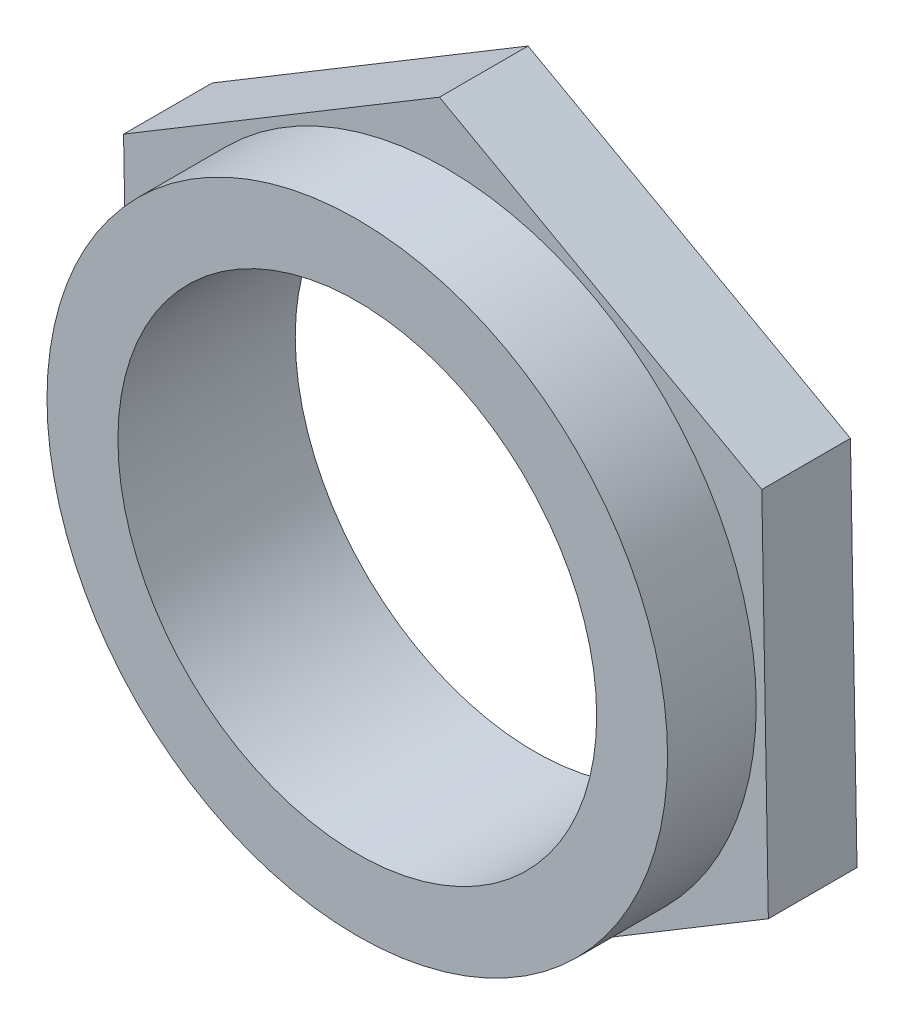
SolidWorks part; units mm, degrees
ref_plane "Front Plane" through (0, 0, 0) normal (0, 0, 1) x (1, 0, 0)
ref_plane "Top Plane" through (0, 0, 0) normal (0, 1, 0) x (1, 0, 0)
ref_plane "Right Plane" through (0, 0, 0) normal (1, 0, 0) x (0, 0, -1)
sketch "Sketch1" plane through (0, 0, 0) normal (0, 0, 1) x (1, 0, 0)
  line L1 (-7.2727, 4.0284) -> (-7.1251, -4.2841)
  line L2 (-7.1251, -4.2841) -> (0.1476, -8.3125)
  line L3 (0.1476, -8.3125) -> (7.2727, -4.0284)
  line L4 (7.2727, -4.0284) -> (7.1251, 4.2841)
  line L5 (7.1251, 4.2841) -> (-0.1476, 8.3125)
  line L6 (-0.1476, 8.3125) -> (-7.2727, 4.0284)
  circle A1 centre (0, 0) radius 7.2 construction
  dimension "D1" = 14.4
extrude "Boss-Extrude1" add sketch "Sketch1" along normal blind 2
sketch "Sketch4" plane through (0, 0, 2) normal (0, 0, 1) x (1, 0, 0)
  circle A0 centre (0, 0) radius 7
  dimension "D1" = 14
extrude "Boss-Extrude2" add sketch "Sketch4" along normal blind 2
hole_wizard "M12x1.25 Tapped Hole2" positions "Sketch6" profile "Sketch5" tap size "M12x1.25" standard "Ansi Metric"
sketch "Sketch6" plane through (0, 0, 4) normal (0, 0, 1) x (1, 0, 0)
  point P0 (0, 0)
sketch "Sketch5" plane through (0, 0, 4) normal (1, 0, 0) x (0, -1, 0)
  line L0 (0, 0) -> (0, 11.9946)
  line L1 (0, 11.9946) -> (5.4, 8.75)
  line L2 (5.4, 8.75) -> (5.4, 0)
  line L5 (5.4, 0) -> (0, 0)
  line L10 (0, 11.9946) -> (-5.4, 8.75) construction
  line L11 (0, -6.35) -> (0, 107.95) construction
  dimension "Tap Drill Dia." = 10.8
  dimension "Tap Drill Depth" = 8.75
  dimension "Drill Angle" = 118
cosmetic thread "Hole Thread2" parameters "D1"=4, "D2"=12
